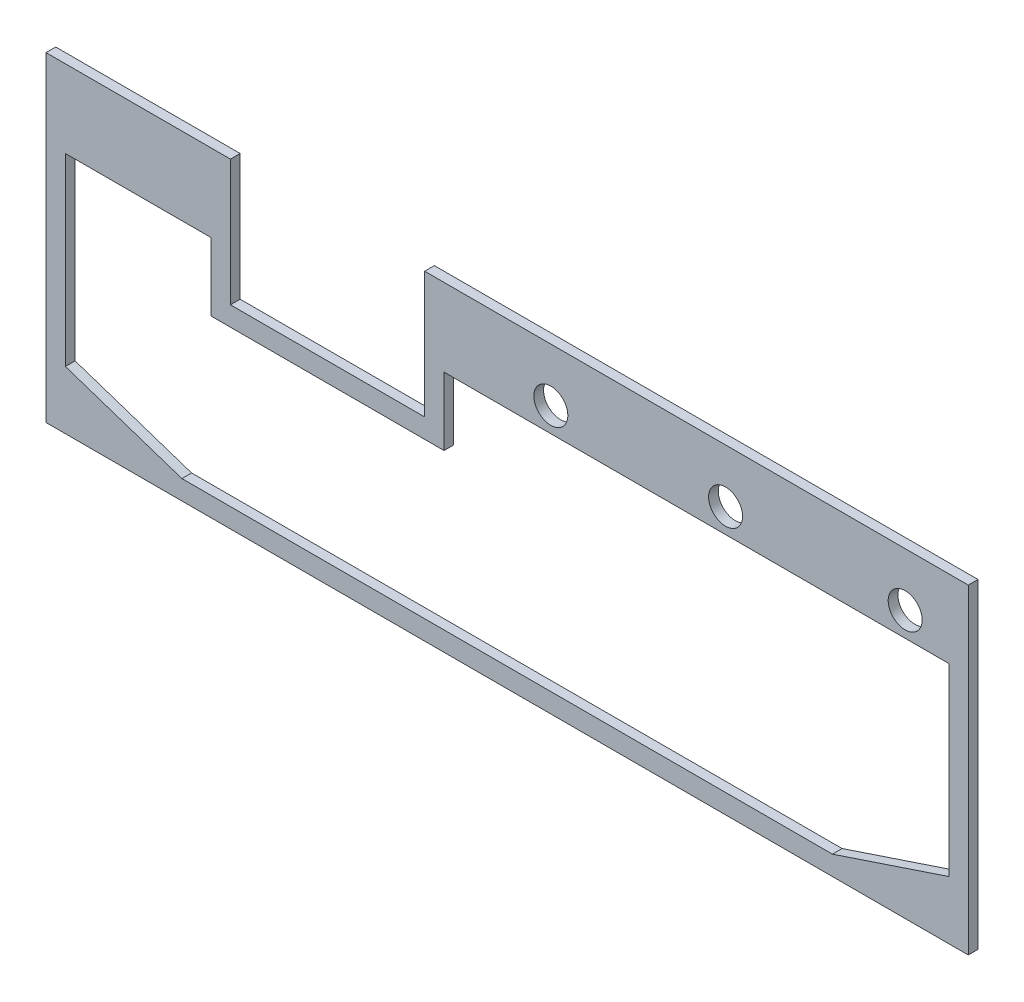
SolidWorks part; units mm, degrees
ref_plane "Front Plane" through (0, 0, 0) normal (0, 0, 1) x (1, 0, 0)
ref_plane "Top Plane" through (0, 0, 0) normal (0, 1, 0) x (1, 0, 0)
ref_plane "Right Plane" through (0, 0, 0) normal (1, 0, 0) x (0, 0, -1)
sketch "Sketch1" plane through (0, 0, 0) normal (0, 0, 1) x (1, 0, 0)
  line L0 (0, 0) -> (0, -19)
  line L5 (0, -19) -> (-12, -23)
  line L6 (-12, -23) -> (-79, -23)
  line L7 (-79, -23) -> (-91, -19)
  line L8 (-91, -19) -> (-91, 0)
  line L9 (-91, 0) -> (-76, 0)
  line L10 (-76, 0) -> (-76, -7)
  line L11 (-76, -7) -> (-52, -7)
  line L12 (-52, -7) -> (-52, 0)
  line L13 (-52, 0) -> (0, 0)
  point P0 (0, 0)
  point P9 (-41.5685, -11.6694)
  point P13 (-31.7314, -17.1896)
  point P14 (-28.5149, -17.4841)
  dimension "D1" = 91
  dimension "D2" = 23
  dimension "D3" = 12
  dimension "D4" = 4
  dimension "D5" = 7
  dimension "D6" = 15
  dimension "D7" = 52
sketch "Sketch2" plane through (0, 0, 0) normal (0, 0, 1) x (1, 0, 0)
  line L0 (-91, -19) -> (-91, 0) construction
  line L2 (2, 8) -> (2, -25)
  line L3 (2, -25) -> (-93, -25)
  line L4 (-93, 8) -> (-93, -25)
  line L5 (-12, -23) -> (-79, -23) construction
  line L6 (0, 0) -> (0, -19) construction
  line L8 (-93, 8) -> (-74, 8)
  line L9 (-74, 8) -> (-74, -5)
  line L10 (-74, -5) -> (-54, -5)
  line L11 (-54, -5) -> (-54, 8)
  line L12 (-54, 8) -> (2, 8)
  line L13 (-91, 0) -> (-76, 0) construction
  line L14 (-76, 0) -> (-76, -7) construction
  line L15 (-76, -7) -> (-52, -7) construction
  line L16 (-52, -7) -> (-52, 0) construction
  dimension "D1" = 2
  dimension "D2" = 2
  dimension "D3" = 2
  dimension "D4" = 8
  dimension "D5" = 2
  dimension "D6" = 2
  dimension "D7" = 2
extrude "Boss-Extrude2" add sketch "Sketch2" along normal blind 1
extrude "Cut-Extrude2" cut sketch "Sketch1" along normal blind 1
hole_wizard "Ø3.0mm Dowel Hole1" positions "Sketch3" profile "Sketch4" hole size "Ø3.0" standard "ANSI Metric" end condition up to next
sketch "Sketch3" plane through (0, 0, 1) normal (0, 0, 1) x (1, 0, 0)
  line L0 (2, -25) -> (2, 8) construction
  line L2 (0, 0) -> (-52, 0) construction
  point P0 (-41, 2.5)
  point P2 (-23, 2.5)
  point P4 (-4.5, 2.5)
  point P9 (0, 0)
  dimension "D1" = 18
  dimension "D2" = 18.5
  dimension "D3" = 6.5
  dimension "D4" = 2.5
sketch "Sketch4" plane through (-41, 2.5, 1) normal (1, 0, 0) x (0, -1, 0)
  line L0 (0, 0) -> (0, 1)
  line L1 (0, 1) -> (1.75, 1)
  line L2 (1.75, 1) -> (1.75, 0)
  line L5 (1.75, 0) -> (0, 0)
  line L11 (0, -6.35) -> (0, 107.95) construction
  dimension "Thru Hole Dia." = 3.5
  dimension "Thru Hole Depth" = 1
